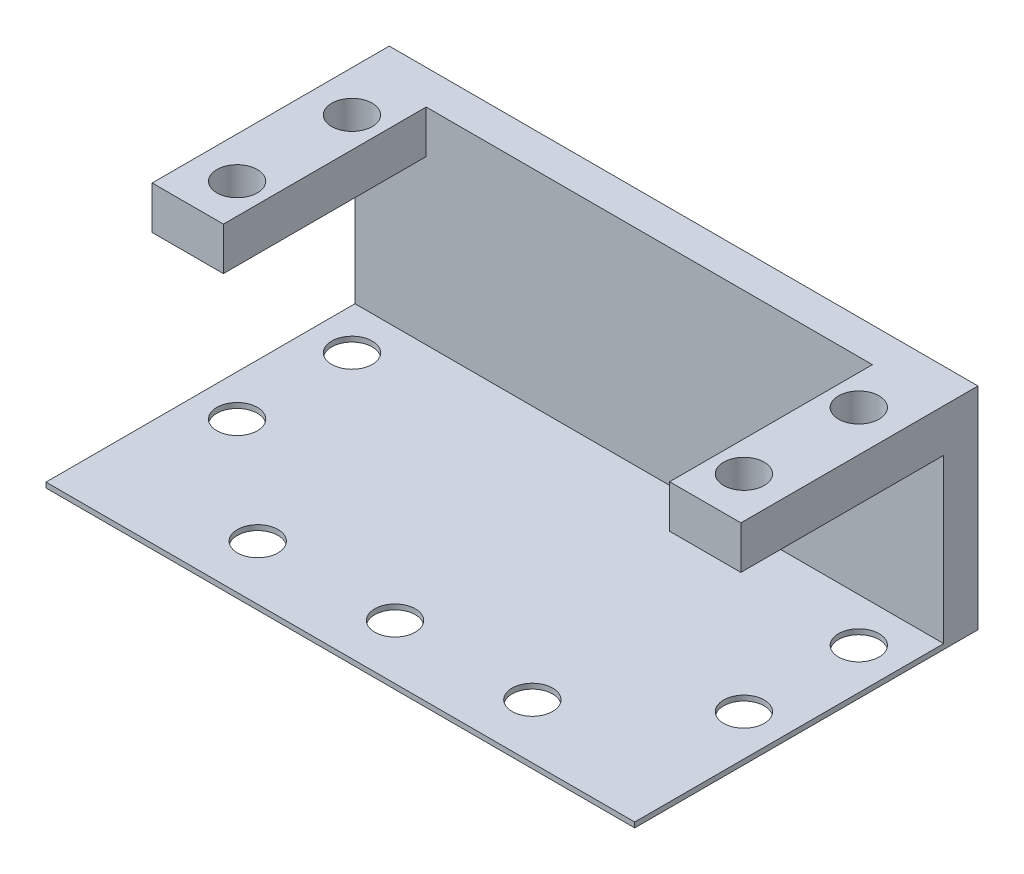
SolidWorks part; units mm, degrees
ref_plane "Front Plane" through (0, 0, 0) normal (0, 0, 1) x (1, 0, 0)
ref_plane "Top Plane" through (0, 0, 0) normal (0, 1, 0) x (1, 0, 0)
ref_plane "Right Plane" through (0, 0, 0) normal (1, 0, 0) x (0, 0, -1)
sketch "Sketch1" plane through (0, 0, 0) normal (0, 1, 0) x (1, 0, 0)
  line L1 (-41.021, 25.4) -> (41.021, 25.4)
  line L2 (-41.021, 25.4) -> (-41.021, -25.4)
  line L3 (-41.021, -25.4) -> (41.021, -25.4)
  line L4 (41.021, 25.4) -> (41.021, -25.4)
  line L5 (-41.021, 25.4) -> (41.021, -25.4) construction
  line L6 (-41.021, -25.4) -> (41.021, 25.4) construction
  point P0 (0, 0)
  dimension "D1" = 82.042
  dimension "D2" = 50.8
extrude "Boss-Extrude1" add sketch "Sketch1" along normal blind 31.242
sketch "Sketch2" plane through (0, 31.242, 0) normal (0, 1, 0) x (1, 0, 0)
  line L0 (41.021, 25.4) -> (-41.021, 25.4) construction
  line L1 (-33.02, 20.32) -> (33.02, 20.32)
  line L2 (-33.02, 20.32) -> (-33.02, -25.4)
  line L3 (-33.02, -25.4) -> (33.02, -25.4)
  line L4 (33.02, 20.32) -> (33.02, -25.4)
  line L5 (-33.02, 20.32) -> (33.02, -25.4) construction
  line L6 (-33.02, -25.4) -> (33.02, 20.32) construction
  line L7 (-41.021, -25.4) -> (41.021, -25.4) construction
  dimension "D1" = 66.04
  dimension "D3" = 5.08
extrude "Cut-Extrude1" cut sketch "Sketch2" against normal blind 30.48
sketch "Sketch3" plane through (0, 31.242, 0) normal (0, 1, 0) x (1, 0, 0)
  circle A0 centre (-37.5, 13.82) radius 3
  circle A1 centre (-37.5, -3.18) radius 3
  circle A2 centre (37.5, 13.82) radius 3
  circle A3 centre (37.5, -3.18) radius 3
extrude "Cut-Extrude2" cut sketch "Sketch3" against normal through all
sketch "Sketch4" plane through (0, 31.242, 0) normal (0, 1, 0) x (1, 0, 0)
  line L0 (-33.02, 20.32) -> (-33.02, -25.4) construction
  line L1 (-41.021, -25.4) -> (-33.02, -25.4)
  line L2 (-41.021, -25.4) -> (-41.021, -9.6887)
  line L3 (-41.021, -9.6887) -> (-33.02, -9.6887)
  line L4 (-33.02, -25.4) -> (-33.02, -9.6887)
  line L5 (0, -25.4) -> (0, 9.0902) construction
  line L6 (-33.02, -25.4) -> (33.02, -25.4) construction
  line L7 (41.021, -9.6887) -> (33.02, -9.6887)
  line L8 (33.02, -25.4) -> (33.02, -9.6887)
  line L9 (41.021, -25.4) -> (33.02, -25.4)
  line L10 (41.021, -25.4) -> (41.021, -9.6887)
extrude "Cut-Extrude3" cut sketch "Sketch4" against normal up to vertex (30.48 mm away)
sketch "Sketch5" plane through (0, 0.762, 0) normal (0, 1, 0) x (1, 0, 0)
  line L0 (-41.021, -9.6887) -> (-41.021, -25.4) construction
  line L3 (-33.02, -9.6887) -> (-41.021, -9.6887) construction
  circle A0 centre (0, -17.3087) radius 3
  circle A1 centre (-37.5, -3.18) radius 3 construction
  circle A2 centre (-20.32, -17.3087) radius 3
  circle A3 centre (20.32, -17.3087) radius 3
  dimension "D1" = 41.021
  dimension "D2" = 20.32
  dimension "D3" = 20.32
  dimension "D4" = 7.62
extrude "Cut-Extrude4" cut sketch "Sketch5" against normal through all
sketch "Sketch6" plane through (41.021, 0, 0) normal (1, 0, 0) x (0, 0, -1)
  line L0 (25.4, 31.242) -> (25.4, 0) construction
  line L1 (-9.6887, 0.762) -> (20.32, 0.762)
  line L2 (-9.6887, 0.762) -> (-9.6887, 24.892)
  line L3 (-9.6887, 24.892) -> (20.32, 24.892)
  line L4 (20.32, 0.762) -> (20.32, 24.892)
  dimension "D1" = 24.13
  dimension "D2" = 5.08
extrude "Cut-Extrude5" cut sketch "Sketch6" against normal through all
sketch "Sketch7" plane through (0, 0.762, 0) normal (0, 1, 0) x (1, 0, 0)
  line L0 (0, 26.4646) -> (0, -33.2045) construction
  circle A0 centre (-36.4578, 6.7339) radius 3.048
  circle A3 centre (36.4578, 6.7339) radius 3.048
  dimension "D1" = 6.096
sketch "Sketch8" plane through (-41.021, 0, 0) normal (-1, 0, 0) x (0, 0, 1)
  line L8 (9.6887, 24.892) -> (9.6887, 31.242)
  line L9 (-20.32, 24.892) -> (9.6887, 24.892)
  line L10 (-20.32, 0.762) -> (-20.32, 24.892)
  line L11 (25.4, 0.762) -> (-20.32, 0.762)
  line L12 (25.4, 0) -> (25.4, 0.762)
  line L13 (-25.4, 0) -> (25.4, 0)
  line L14 (-25.4, 31.242) -> (-25.4, 0)
  line L15 (9.6887, 31.242) -> (-25.4, 31.242)
  line L16 (9.6887, 24.892) -> (9.6887, 31.242)
  line L17 (-20.32, 24.892) -> (9.6887, 24.892)
  line L18 (-20.32, 0.762) -> (-20.32, 24.892)
  line L19 (25.4, 0.762) -> (-20.32, 0.762)
  line L20 (25.4, 0) -> (25.4, 0.762)
  line L21 (-25.4, 0) -> (25.4, 0)
  line L22 (-25.4, 31.242) -> (-25.4, 0)
  line L23 (9.6887, 31.242) -> (-25.4, 31.242)
  dimension "D1" = 0
extrude "Boss-Extrude2" add sketch "Sketch8" along normal blind 2.54
sketch "Sketch9" plane through (41.021, 0, 0) normal (1, 0, 0) x (0, 0, -1)
  line L8 (-9.6887, 31.242) -> (-9.6887, 24.892)
  line L9 (-9.6887, 24.892) -> (20.32, 24.892)
  line L10 (20.32, 24.892) -> (20.32, 0.762)
  line L11 (20.32, 0.762) -> (-25.4, 0.762)
  line L12 (-25.4, 0.762) -> (-25.4, 0)
  line L13 (-25.4, 0) -> (25.4, 0)
  line L14 (25.4, 0) -> (25.4, 31.242)
  line L15 (25.4, 31.242) -> (-9.6887, 31.242)
  line L16 (-9.6887, 31.242) -> (-9.6887, 24.892)
  line L17 (-9.6887, 24.892) -> (20.32, 24.892)
  line L18 (20.32, 24.892) -> (20.32, 0.762)
  line L19 (20.32, 0.762) -> (-25.4, 0.762)
  line L20 (-25.4, 0.762) -> (-25.4, 0)
  line L21 (-25.4, 0) -> (25.4, 0)
  line L22 (25.4, 0) -> (25.4, 31.242)
  line L23 (25.4, 31.242) -> (-9.6887, 31.242)
  dimension "D1" = 0
extrude "Boss-Extrude3" add sketch "Sketch9" along normal blind 2.54
